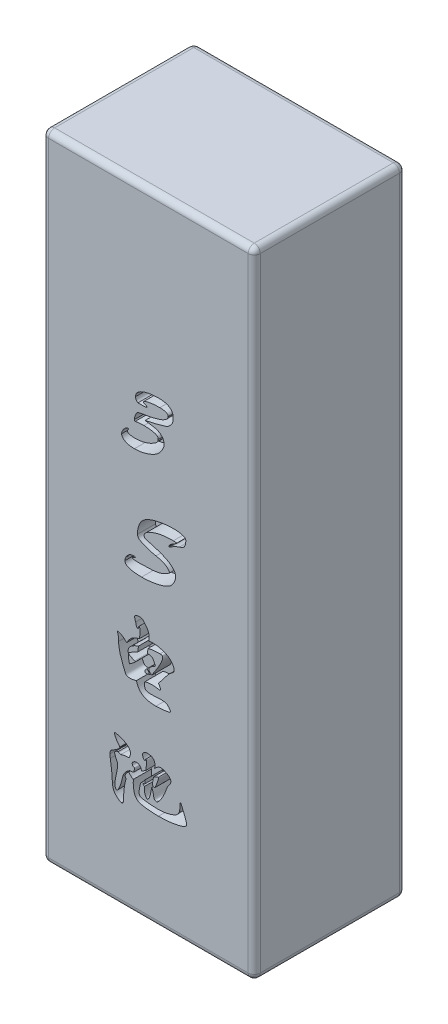
SolidWorks part; units mm, degrees
ref_plane "前视基准面" through (0, 0, 0) normal (0, 0, 1) x (1, 0, 0)
ref_plane "上视基准面" through (0, 0, 0) normal (0, 1, 0) x (1, 0, 0)
ref_plane "右视基准面" through (0, 0, 0) normal (1, 0, 0) x (0, 0, -1)
sketch "草图1" plane through (0, 0, 0) normal (0, 1, 0) x (1, 0, 0)
  line L1 (-17.5, 12.5) -> (17.5, 12.5)
  line L2 (-17.5, 12.5) -> (-17.5, -12.5)
  line L3 (-17.5, -12.5) -> (17.5, -12.5)
  line L4 (17.5, 12.5) -> (17.5, -12.5)
  line L5 (-17.5, 12.5) -> (17.5, -12.5) construction
  line L6 (-17.5, -12.5) -> (17.5, 12.5) construction
  point P0 (0, 0)
  dimension "D1" = 35
  dimension "D2" = 25
extrude "凸台-拉伸1" add sketch "草图1" along normal blind 105
sketch "草图2" plane through (0, 0, 12.5) normal (0, 0, 1) x (1, 0, 0)
  text T0 " 3\r\n S\r\n电\r\n池" font "华文行楷" height 10
extrude "切除-拉伸1" cut sketch "草图2" against normal blind 3
fillet "圆角1" radius 1 12 edges at (0, 0, -12.5) (-17.5, 0, 0) (0, 0, 12.5) (17.5, 0, 0) (0, 105, 12.5) (-17.5, 105, 0) (0, 105, -12.5) (17.5, 105, 0) (-17.5, 52.5, -12.5) (17.5, 52.5, -12.5) (17.5, 52.5, 12.5) (-17.5, 52.5, 12.5)
